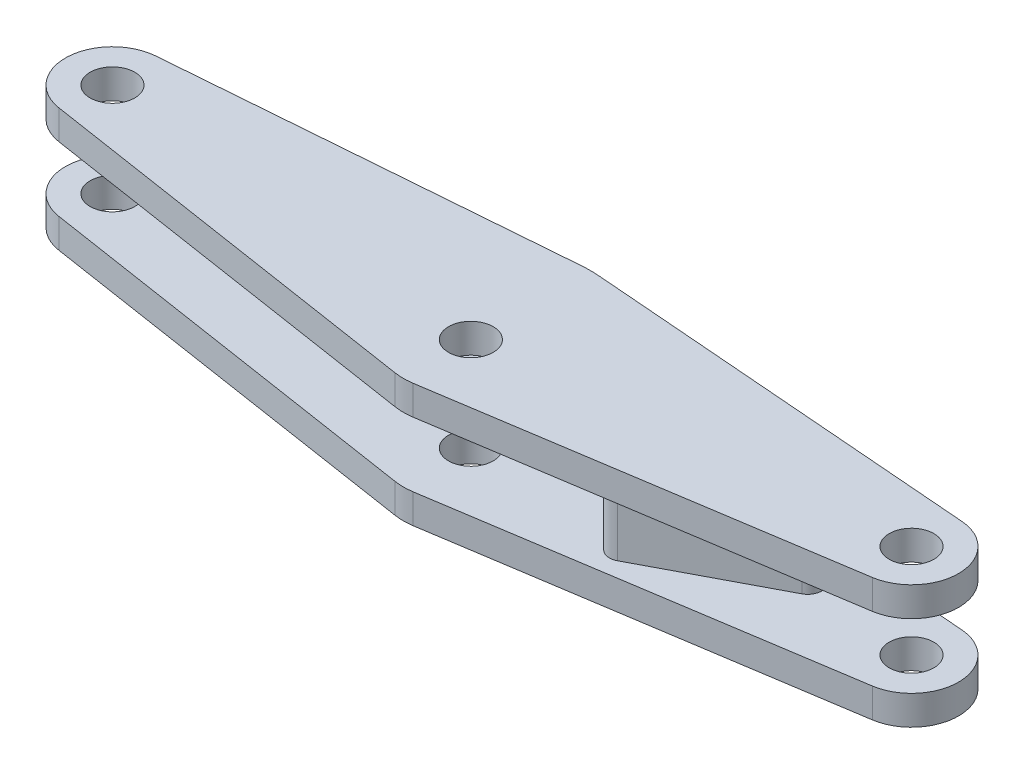
SolidWorks part; units mm, degrees
ref_plane "Front Plane" through (0, 0, 0) normal (0, 0, 1) x (1, 0, 0)
ref_plane "Top Plane" through (0, 0, 0) normal (0, 1, 0) x (1, 0, 0)
ref_plane "Right Plane" through (0, 0, 0) normal (1, 0, 0) x (0, 0, -1)
sketch "Sketch1" plane through (0, 0, 0) normal (0, 1, 0) x (1, 0, 0)
  line L0 (-17, 0) -> (17, 0) construction
  line L1 (0, 3.35) -> (0, -4.65) construction
  line L2 (-0.394, 3.3189) -> (-17.1576, 1.9938)
  line L3 (-0.3817, -4.591) -> (-17.3054, -1.9766)
  line L4 (0.3817, -4.591) -> (17.3054, -1.9766)
  line L5 (0.394, 3.3189) -> (17.1576, 1.9938)
  arc A0 (-17.1576, 1.9938) -> (-17.3054, -1.9766) centre (-17, 0) ccw
  circle A1 centre (-17, 0) radius 0.95
  circle A2 centre (17, 0) radius 0.95
  arc A3 (17.1576, 1.9938) -> (17.3054, -1.9766) centre (17, 0) cw
  arc A4 (0.394, 3.3189) -> (-0.394, 3.3189) centre (0, -1.6656) ccw
  arc A5 (0.3817, -4.591) -> (-0.3817, -4.591) centre (0, -2.1203) cw
  circle A6 centre (0, -1.75) radius 0.95
  point P5 (0, 0)
  dimension "D4" = 4
  dimension "D5" = 1.9
  dimension "D6" = 5
  dimension "D7" = 2.5
  dimension "D8" = 1.9
  dimension "D9" = 1.75
  dimension "D1" = 34
  dimension "D2" = 8
  dimension "D3" = 3.35
extrude "Boss-Extrude1" add sketch "Sketch1" along normal mid plane 5.25
sketch "Sketch2" plane through (0, 0, 0) normal (0, 0, 1) x (1, 0, 0)
  line L0 (-19, 2.625) -> (-19, -2.625) construction
  line L1 (19, 1.375) -> (-19, 1.375)
  line L2 (19, 1.375) -> (19, -1.375)
  line L3 (19, -1.375) -> (-19, -1.375)
  line L4 (-19, 1.375) -> (-19, -1.375)
  line L5 (19, 1.375) -> (-19, -1.375) construction
  line L6 (19, -1.375) -> (-19, 1.375) construction
  line L7 (-17.3054, 2.625) -> (-0.3817, 2.625) construction
  point P0 (0, 0)
  dimension "D1" = 1.25
extrude "Cut-Extrude1" cut sketch "Sketch2" against normal blind 5.25 and the other way through all
sketch "Sketch3" plane through (0, 0, 0) normal (0, 1, 0) x (1, 0, 0)
  line L0 (0, 0) -> (11.9545, 0) construction
  line L1 (1.8714, 0.45) -> (12.1332, 0.45) construction
  line L2 (12.1332, 0.45) -> (7, -2.25) construction
  line L3 (12.4125, -0.081) -> (7.2793, -2.781)
  line L4 (11.8539, 0.981) -> (6.7207, -1.719)
  arc A0 (12.4125, -0.081) -> (11.8539, 0.981) centre (12.1332, 0.45) ccw
  arc A1 (6.7207, -1.719) -> (7.2793, -2.781) centre (7, -2.25) ccw
  point P5 (9.5666, -0.9)
  dimension "D1" = 0.6
  dimension "D2" = 5.8
  dimension "D3" = 0.45
  dimension "D4" = 2.25
  dimension "D5" = 7
extrude "Boss-Extrude2" add sketch "Sketch3" along normal up to next (2.625 mm away) and the other way up to next (1.375 mm away)
